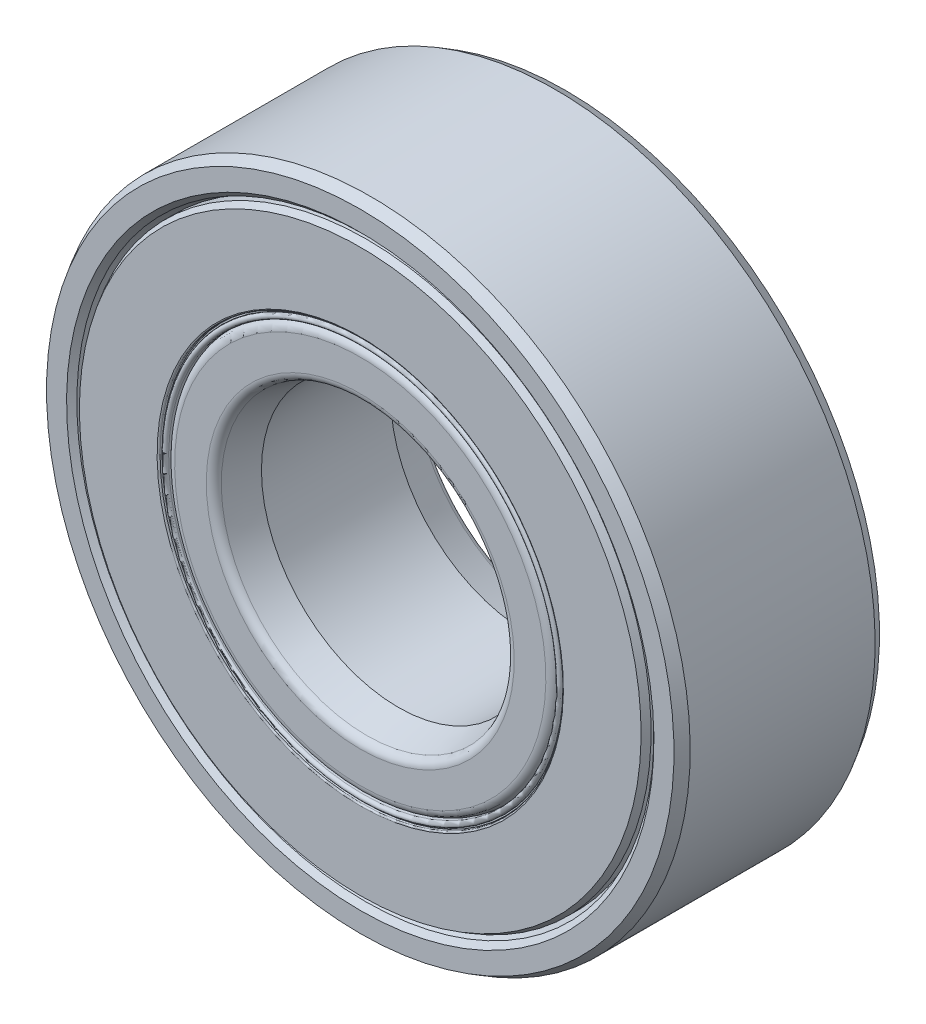
SolidWorks part; units mm, degrees
ref_plane "Front Plane" through (0, 0, 0) normal (0, 0, 1) x (1, 0, 0)
ref_plane "Top Plane" through (0, 0, 0) normal (0, 1, 0) x (1, 0, 0)
ref_plane "Right Plane" through (0, 0, 0) normal (1, 0, 0) x (0, 0, -1)
sketch "Sketch1" plane through (0, 0, 0) normal (0, 0, 1) x (1, 0, 0)
  line L0 (-11.1125, 0) -> (11.1125, 0) construction
  line L1 (-4.7625, 0) -> (4.7625, 0) construction
  circle A0 centre (0, 0) radius 4.7625 construction
  circle A1 centre (0, 0) radius 11.1125 construction
  point P3 (0, 0)
  point P6 (0, 0)
  point P7 (0, -4.7625)
  point P11 (0, -11.1125)
  point P12 (0, 4.7625)
  point P13 (0, 11.1125)
  dimension "OD" = 22.225
  dimension "ID" = 9.525
sketch "Sketch2" plane through (0, 0, 0) normal (1, 0, 0) x (0, 0, -1)
  line L0 (-3.5719, 11.1125) -> (3.5719, 11.1125) construction
  line L1 (0, 11.1125) -> (0, -11.1125) construction
  line L2 (3.2147, 11.1125) -> (-3.2147, 11.1125)
  line L3 (-3.2147, 11.1125) -> (-3.5719, 10.9063)
  line L4 (-3.5719, 10.9063) -> (-3.5719, 10.2098)
  line L5 (-3.0057, 9.8901) -> (-1.7936, 9.8901)
  line L6 (3.0057, 9.8901) -> (1.7936, 9.8901)
  line L7 (3.5719, 10.9063) -> (3.5719, 10.2098)
  line L8 (3.2147, 11.1125) -> (3.5719, 10.9063)
  line L9 (-1.7936, 9.8901) -> (-1.7936, 10.2976) construction
  line L10 (-1.7936, 10.2976) -> (-1.7936, 10.705) construction
  line L11 (0, 11.1125) -> (0, -11.1125) construction
  line L12 (-3.5719, 0) -> (3.5719, 0) construction
  line L13 (3.5719, 4.7625) -> (-3.5719, 4.7625) construction
  line L14 (-3.5719, 4.7625) -> (-3.5719, -4.7625) construction
  line L15 (-3.5719, -4.7625) -> (3.5719, -4.7625) construction
  line L16 (3.5719, 11.1125) -> (3.5719, -11.1125) construction
  line L17 (-1.7936, 10.705) -> (-1.7936, 11.1125) construction
  line L18 (-1.7936, 10.705) -> (0, 10.705) construction
  line L20 (-3.0057, 9.8901) -> (-3.3933, 10.0312)
  line L21 (-3.3933, 10.0312) -> (-3.5719, 10.2098)
  line L26 (3.3933, 10.0312) -> (3.5719, 10.2098)
  line L27 (3.0057, 9.8901) -> (3.3933, 10.0312)
  arc A0 (-1.7936, 9.8901) -> (1.7936, 9.8901) centre (0, 8.3238) cw
  circle A1 centre (0, 8.3238) radius 2.3813 construction
  point P17 (0, 0)
  point P21 (0, 11.1125)
  point P30 (0, -4.7625)
  dimension "Approx. Ball Dia." = 4.7625
  dimension "Width" = 7.1437
  dimension "For Shaft Diameter" = 9.525
  dimension "For Housing ID" = 22.225
  dimension "D4" = 19.7802
  dimension "D2" = 20
  dimension "D5" = 45
  dimension "D1" = 30
  dimension "D6" = 0.3572
  dimension "D7" = 0.1786
sketch "Sketch3" plane through (0, 0, 0) normal (1, 0, 0) x (0, 0, -1)
  line L14 (-3.0057, 9.8901) -> (-3.3933, 10.0312) construction
  line L15 (-3.3933, 10.0312) -> (-3.5719, 10.2098) construction
  line L16 (-3.5719, 10.9063) -> (-3.5719, 10.2098) construction
  line L17 (-3.2147, 11.1125) -> (-3.5719, 10.9063) construction
  line L18 (3.2147, 11.1125) -> (-3.2147, 11.1125) construction
  line L19 (3.2147, 11.1125) -> (3.5719, 10.9063) construction
  line L20 (3.5719, 10.9063) -> (3.5719, 10.2098) construction
  line L21 (3.3933, 10.0312) -> (3.5719, 10.2098) construction
  line L22 (3.0057, 9.8901) -> (3.3933, 10.0312) construction
  line L23 (3.0057, 9.8901) -> (1.7936, 9.8901) construction
  line L24 (-3.0057, 9.8901) -> (-1.7936, 9.8901) construction
  line L25 (-3.0057, 9.8901) -> (-3.3933, 10.0312)
  line L26 (-3.3933, 10.0312) -> (-3.5719, 10.2098)
  line L27 (-3.5719, 10.9063) -> (-3.5719, 10.2098)
  line L28 (-3.2147, 11.1125) -> (-3.5719, 10.9063)
  line L29 (3.2147, 11.1125) -> (-3.2147, 11.1125)
  line L30 (3.2147, 11.1125) -> (3.5719, 10.9063)
  line L31 (3.5719, 10.9063) -> (3.5719, 10.2098)
  line L32 (3.3933, 10.0312) -> (3.5719, 10.2098)
  line L33 (3.0057, 9.8901) -> (3.3933, 10.0312)
  line L34 (3.0057, 9.8901) -> (1.7936, 9.8901)
  line L35 (-3.0057, 9.8901) -> (-1.7936, 9.8901)
  arc A2 (1.7936, 9.8901) -> (-1.7936, 9.8901) centre (0, 8.3238) ccw construction
  arc A3 (1.7936, 9.8901) -> (-1.7936, 9.8901) centre (0, 8.3238) ccw
revolve "Revolve1" add sketch "Sketch3" angle 360 about L12
sketch "Sketch4" plane through (0, 0, 0) normal (1, 0, 0) x (0, 0, -1)
  line L0 (0, 11.1125) -> (0, -11.1125) construction
  line L1 (0, 11.1125) -> (0, -11.1125) construction
  line L2 (-2.2445, 4.7625) -> (-3.3455, 5.0575)
  line L3 (-3.5719, 5.3525) -> (-3.5719, 6.452)
  line L4 (3.5719, -10.9063) -> (3.5719, 10.9063) construction
  line L5 (-3.2665, 6.7575) -> (-1.7936, 6.7575)
  line L6 (-2.2445, 4.7625) -> (2.2445, 4.7625)
  line L7 (3.5719, 10.9063) -> (3.5719, 10.2098) construction
  line L8 (2.2445, 4.7625) -> (3.3455, 5.0575)
  line L9 (0, 10.705) -> (0, 4.7625) construction
  line L10 (3.5719, 5.3525) -> (3.5719, 6.452)
  line L11 (3.2665, 6.7575) -> (1.7936, 6.7575)
  line L12 (2.2445, 4.7625) -> (2.2445, 5.0575) construction
  line L13 (2.2445, 5.0575) -> (2.2445, 5.3525) construction
  line L14 (2.2445, 5.3525) -> (2.2445, 5.6475) construction
  line L15 (2.2445, 5.6475) -> (2.2445, 5.9425) construction
  circle A0 centre (0, 8.3238) radius 2.3812 construction
  arc A1 (1.7936, 6.7575) -> (-1.7936, 6.7575) centre (0, 8.3238) cw
  arc A2 (3.5719, 6.452) -> (3.2665, 6.7575) centre (3.2665, 6.452) ccw
  arc A3 (-3.5719, 6.452) -> (-3.2665, 6.7575) centre (-3.2665, 6.452) cw
  arc A4 (3.3455, 5.0575) -> (3.5719, 5.3525) centre (3.2665, 5.3525) ccw
  arc A5 (-3.3455, 5.0575) -> (-3.5719, 5.3525) centre (-3.2665, 5.3525) cw
  point P14 (3.5719, 5.1182)
  point P36 (0, 5.9425)
  dimension "D1" = 15
revolve "Revolve2" add sketch "Sketch4" angle 360 about L12
sketch "Sketch5" plane through (0, 0, 0) normal (1, 0, 0) x (0, 0, -1)
  line L0 (-2.3812, 8.3238) -> (2.3812, 8.3238)
  arc A2 (-2.3812, 8.3238) -> (2.3812, 8.3238) centre (0, 8.3238) cw
  arc A3 (1.7936, 9.8901) -> (-1.7936, 9.8901) centre (0, 8.3238) ccw construction
revolve "Revolve3" add sketch "Sketch5" angle 360 about L0
pattern_circular "CirPattern1" count 8 over 360 about axis through (0, 0, 0) along (0, 0, 1) of bodies 104
sketch "Sketch6" plane through (0, 0, 0) normal (1, 0, 0) x (0, 0, -1)
  line L1 (-3.3519, 9.8901) -> (-2.3812, 9.8901)
  line L2 (-3.5719, 9.7631) -> (-3.5719, 7.0623)
  line L3 (-3.5211, 7.0115) -> (-2.3812, 7.0115)
  line L4 (-2.3812, 9.8901) -> (-2.3812, 7.0115)
  line L5 (-3.5719, 5.3525) -> (-3.5719, 6.452) construction
  line L6 (-3.2147, 11.1125) -> (-3.5719, 10.9063) construction
  line L7 (0, 11.1125) -> (0, 4.7625) construction
  line L8 (3.5211, 7.0115) -> (2.3813, 7.0115)
  line L9 (2.3813, 9.8901) -> (2.3813, 7.0115)
  line L10 (3.3519, 9.8901) -> (2.3813, 9.8901)
  line L11 (3.5719, 9.7631) -> (3.5719, 7.0623)
  line L13 (-3.2665, 6.7575) -> (-1.7936, 6.7575) construction
  line L14 (-3.5719, 9.7631) -> (-3.3519, 9.8901)
  line L15 (-3.0057, 9.8901) -> (-1.7936, 9.8901) construction
  line L16 (3.5719, 9.7631) -> (3.3519, 9.8901)
  arc A0 (-3.5719, 7.0623) -> (-3.5211, 7.0115) centre (-3.5211, 7.0623) ccw
  circle A1 centre (0, 8.3238) radius 2.3812 construction
  arc A2 (3.5719, 7.0623) -> (3.5211, 7.0115) centre (3.5211, 7.0623) cw
  point P26 (-3.5719, 7.0115)
  dimension "D3" = 0.0508
  dimension "D1" = 0.254
  dimension "D2" = 0.127
revolve "Revolve4" add sketch "Sketch6" angle 360 about L12
sketch "Sketch7" plane through (0, 0, 0) normal (1, 0, 0) x (0, 0, -1)
  line L3 (-2.3812, 7.0115) -> (-3.3937, 7.0115)
  line L4 (-3.5211, 7.0115) -> (-2.3812, 7.0115) construction
  line L7 (0, 5.9425) -> (0, 4.7625) construction
  line L8 (0, 11.1125) -> (0, -11.1125) construction
  line L21 (-3.3937, 7.0115) -> (-3.4562, 7.0004)
  line L22 (-3.4516, 6.948) -> (-3.4766, 6.948)
  line L23 (-3.4766, 6.7575) -> (-2.3812, 6.7575)
  line L24 (-2.3812, 6.7575) -> (-2.3812, 7.0115)
  line L25 (-3.2665, 6.7575) -> (-1.7936, 6.7575) construction
  line L26 (-3.5719, 7.0623) -> (-3.5719, 6.7575) construction
  line L27 (-3.5719, 6.7575) -> (-3.4766, 6.7575) construction
  line L28 (-3.3937, 7.0115) -> (-3.3937, 6.948) construction
  line L29 (-3.3937, 6.948) -> (-3.3937, 6.8845) construction
  line L30 (-3.3937, 6.8845) -> (-3.3937, 6.821) construction
  line L31 (-3.3937, 6.821) -> (-3.3937, 6.7575) construction
  circle A2 centre (0, 8.3238) radius 2.3812 construction
  arc A9 (-3.4562, 7.0004) -> (-3.4516, 6.948) centre (-3.4516, 6.9744) ccw
  arc A10 (-3.4766, 6.948) -> (-3.4766, 6.7575) centre (-3.4766, 6.8527) ccw
  dimension "D1" = 0.025
  dimension "D2" = 10
revolve "Revolve5" add sketch "Sketch7" angle 360 about L12
equation "\"D4@Sketch2\"=\"OD@Sketch1\"*.89"
equation "\"D1@Sketch6\"=(\"OD@Sketch1\"-\"ID@Sketch1\")*.02"
equation "\"D2@Sketch6\"=\"D1@Sketch6\"*.5"
equation "\"D3@Sketch6\"=\"D1@Sketch6\"*.2"
equation "\"D6@Sketch2\"=\"Width@Sketch2\"*.05"
equation "\"D7@Sketch2\"=\"D6@Sketch2\"*.5"
equation "\"D1@CirPattern1\" =  ( pi * \"OD@Sketch1\" )  * .5625 / \"Approx. Ball Dia.@Sketch2\""
equation "\"Approx. Ball Dia.@Sketch2\"=(\"OD@Sketch1\"-\"ID@Sketch1\")*.5*.75"
